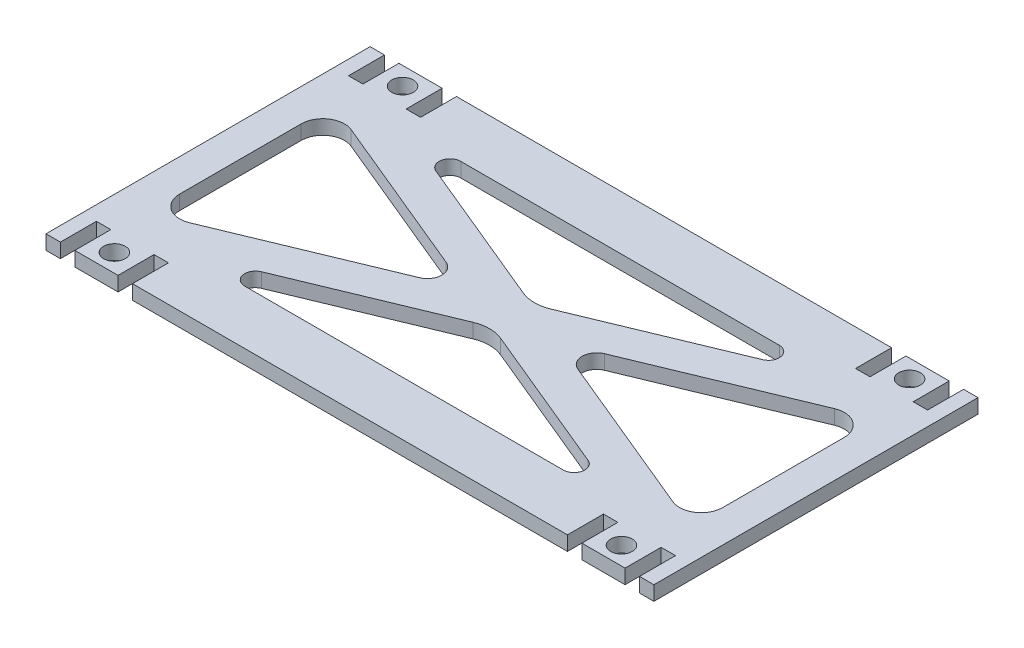
SolidWorks part; units mm, degrees
ref_plane "Front Plane" through (0, 0, 0) normal (0, 0, 1) x (1, 0, 0)
ref_plane "Top Plane" through (0, 0, 0) normal (0, 1, 0) x (1, 0, 0)
ref_plane "Right Plane" through (0, 0, 0) normal (1, 0, 0) x (0, 0, -1)
sketch "Sketch1" plane through (0, 0, 0) normal (0, 1, 0) x (1, 0, 0)
  line L0 (42.2, 45) -> (42.2, 0) construction
  line L1 (0, 0) -> (2, 0)
  line L2 (0, 0) -> (0, 45)
  line L3 (0, 45) -> (2, 45)
  line L4 (84.4, 0) -> (84.4, 45)
  line L5 (0, 22.5) -> (84.4, 22.5) construction
  line L6 (7, 45) -> (7, 42.5) construction
  line L7 (7, 42.5) -> (11, 42.5) construction
  line L9 (10, 40) -> (12, 40)
  line L10 (10, 40) -> (10, 45)
  line L12 (12, 40) -> (12, 45)
  line L13 (10, 40) -> (12, 45) construction
  line L14 (10, 45) -> (12, 40) construction
  line L15 (2, 40) -> (2, 45)
  line L16 (4, 40) -> (2, 40)
  line L17 (4, 40) -> (4, 45)
  line L19 (72.4, 40) -> (72.4, 45)
  line L20 (74.4, 40) -> (72.4, 40)
  line L21 (74.4, 40) -> (74.4, 45)
  line L22 (80.4, 40) -> (80.4, 45)
  line L23 (80.4, 40) -> (82.4, 40)
  line L24 (82.4, 40) -> (82.4, 45)
  line L27 (12, 5) -> (12, 0)
  line L28 (10, 5) -> (12, 5)
  line L29 (10, 5) -> (10, 0)
  line L30 (4, 5) -> (4, 0)
  line L31 (4, 5) -> (2, 5)
  line L32 (2, 5) -> (2, 0)
  line L35 (82.4, 5) -> (82.4, 0)
  line L36 (80.4, 5) -> (82.4, 5)
  line L37 (80.4, 5) -> (80.4, 0)
  line L38 (74.4, 5) -> (74.4, 0)
  line L39 (74.4, 5) -> (72.4, 5)
  line L40 (72.4, 5) -> (72.4, 0)
  line L42 (4, 0) -> (10, 0)
  line L43 (12, 0) -> (72.4, 0)
  line L44 (4, 45) -> (10, 45)
  line L45 (12, 45) -> (72.4, 45)
  line L46 (82.4, 45) -> (84.4, 45)
  line L47 (74.4, 45) -> (80.4, 45)
  line L48 (82.4, 0) -> (84.4, 0)
  line L49 (74.4, 0) -> (80.4, 0)
  circle A0 centre (7, 42.5) radius 1.5
  circle A1 centre (77.4, 42.5) radius 1.5
  circle A2 centre (7, 2.5) radius 1.5
  circle A3 centre (77.4, 2.5) radius 1.5
  dimension "D3" = 3
  dimension "D1" = 84.4
  dimension "D2" = 45
  dimension "D4" = 2
  dimension "D5" = 5
  dimension "D7" = 2
  dimension "D8" = 6
extrude "Boss-Extrude1" add sketch "Sketch1" along normal blind 2
sketch "Sketch3" plane through (0, 2, 0) normal (0, 1, 0) x (1, 0, 0)
  line L0 (42.2, 45) -> (42.2, 0) construction
  line L1 (72.4, 45) -> (12, 45) construction
  line L2 (12, 0) -> (72.4, 0) construction
  line L3 (0, 22.5) -> (84.4, 22.5) construction
  line L4 (0, 45) -> (0, 0) construction
  line L5 (84.4, 0) -> (84.4, 45) construction
  line L6 (2, 5) -> (0, 5) construction
  line L7 (0, 5) -> (42.2, 22.5) construction
  line L8 (71.845, 7.5) -> (12.555, 7.5)
  line L9 (12.555, 7.5) -> (42.2, 19.7936)
  line L10 (4.5, 35.4274) -> (4.5, 9.5726)
  line L11 (4.5, 9.5726) -> (35.6736, 22.5)
  line L12 (10, 5) -> (12, 5) construction
  line L13 (2, 0) -> (2, 5) construction
  line L14 (12.555, 37.5) -> (42.2, 25.2064)
  line L15 (71.845, 37.5) -> (12.555, 37.5)
  line L16 (4.5, 35.4274) -> (35.6736, 22.5)
  line L17 (71.845, 7.5) -> (42.2, 19.7936)
  line L18 (71.845, 37.5) -> (42.2, 25.2064)
  line L19 (79.9, 35.4274) -> (79.9, 9.5726)
  line L20 (79.9, 9.5726) -> (48.7264, 22.5)
  line L21 (79.9, 35.4274) -> (48.7264, 22.5)
  point P30 (4.5, 22.5)
  point P31 (42.2, 7.5)
  point P32 (42.2, 37.5)
  dimension "D1" = 2.5
  dimension "D2" = 2.5
  dimension "D3" = 2.5
  dimension "D4" = 2.5
extrude "Cut-Extrude2" cut sketch "Sketch3" against normal blind 10
fillet "Fillet30" radius 1.5 4 edges at (71.845, 1, -37.5) (71.845, 1, -7.5) (12.555, 1, -7.5) (12.555, 1, -37.5)
fillet "Fillet31" radius 5 2 edges at (42.2, 1, -19.7936) (42.2, 1, -25.2064)
fillet "Fillet32" radius 2 2 edges at (35.6736, 1, -22.5) (48.7264, 1, -22.5)
fillet "Fillet33" radius 3 4 edges at (4.5, 1, -9.5726) (4.5, 1, -35.4274) (79.9, 1, -9.5726) (79.9, 1, -35.4274)
